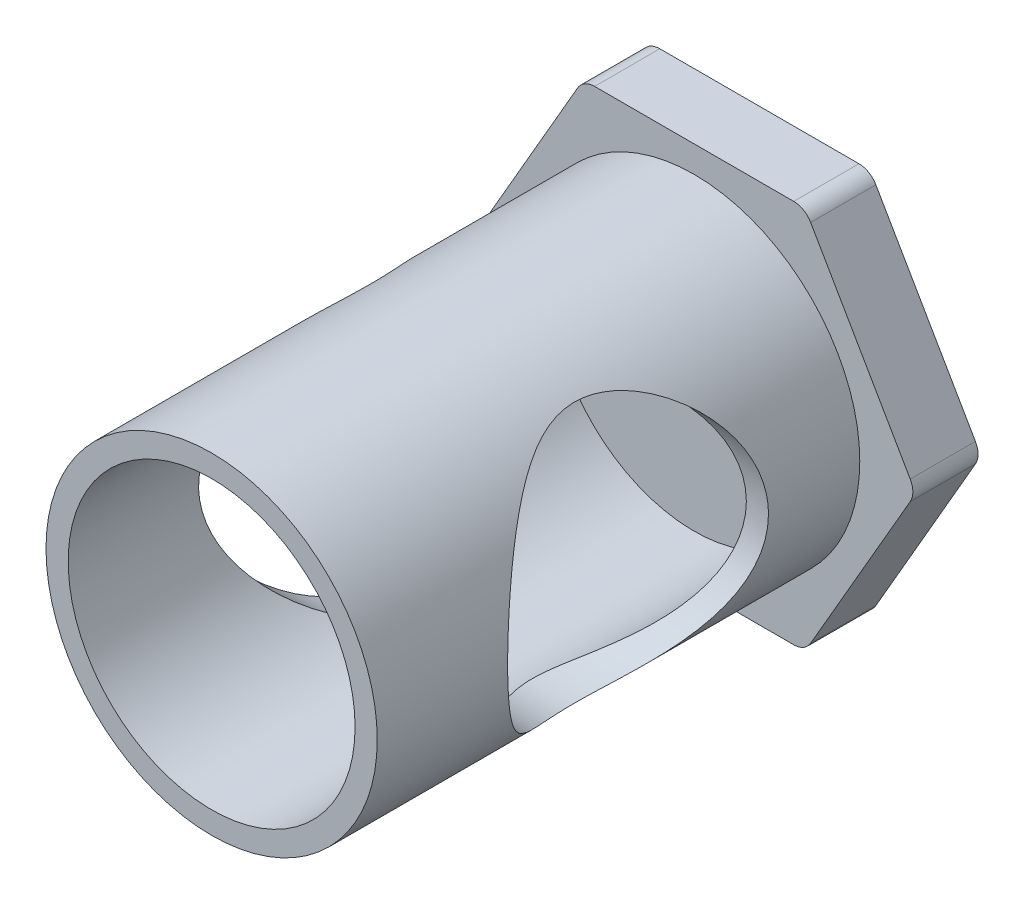
SolidWorks part; units mm, degrees
ref_plane "Front Plane" through (0, 0, 0) normal (0, 0, 1) x (1, 0, 0)
ref_plane "Top Plane" through (0, 0, 0) normal (0, 1, 0) x (1, 0, 0)
ref_plane "Right Plane" through (0, 0, 0) normal (1, 0, 0) x (0, 0, -1)
sketch "Sketch1" plane through (0, 0, 0) normal (0, 0, 1) x (1, 0, 0)
  line L0 (0, 0) -> (8.5, 0) construction
  line L1 (8.5, 0) -> (4.25, 7.3612)
  line L2 (4.25, 7.3612) -> (-4.25, 7.3612)
  line L3 (-4.25, 7.3612) -> (-8.5, 0)
  line L4 (-8.5, 0) -> (-4.25, -7.3612)
  line L5 (-4.25, -7.3612) -> (4.25, -7.3612)
  line L6 (4.25, -7.3612) -> (8.5, 0)
  circle A0 centre (0, 0) radius 7.3612 construction
  dimension "D1" = 8.5
extrude "Boss-Extrude1" add sketch "Sketch1" along normal blind 2.5
sketch "Sketch2" plane through (0, 0, 2.5) normal (0, 0, 1) x (1, 0, 0)
  circle A0 centre (0, 0) radius 6.35
  dimension "D1" = 12.7
extrude "Boss-Extrude2" add sketch "Sketch2" along normal blind 18.5
sketch "Sketch3" plane through (0, 0, 21) normal (0, 0, 1) x (1, 0, 0)
  circle A0 centre (0, 0) radius 5.5
  dimension "D1" = 11
extrude "Cut-Extrude3" cut sketch "Sketch3" against normal up to surface (18.5 mm away) up to face at (6.35, 0, 2.5)
ref_plane "Plane1" through (-6.35, 0, 0) normal (-1, 0, 0) x (0, 0, 1)
sketch "Sketch4" plane through (-6.35, 0, 0) normal (-1, 0, 0) x (0, 0, 1)
  line L0 (2.5, 0) -> (19.5, 0) construction
  line L1 (2.5, -6.35) -> (2.5, 6.35) construction
  circle A0 centre (11, 0) radius 5
  dimension "D1" = 10
  dimension "D2" = 17
extrude "Cut-Extrude4" cut sketch "Sketch4" against normal through all contours A0
fillet "Fillet1" radius 0.75 6 edges at (-4.25, 7.3612, 1.25) (-8.5, 0, 1.25) (-4.25, -7.3612, 1.25) (4.25, -7.3612, 1.25) (8.5, 0, 1.25) (4.25, 7.3612, 1.25)
